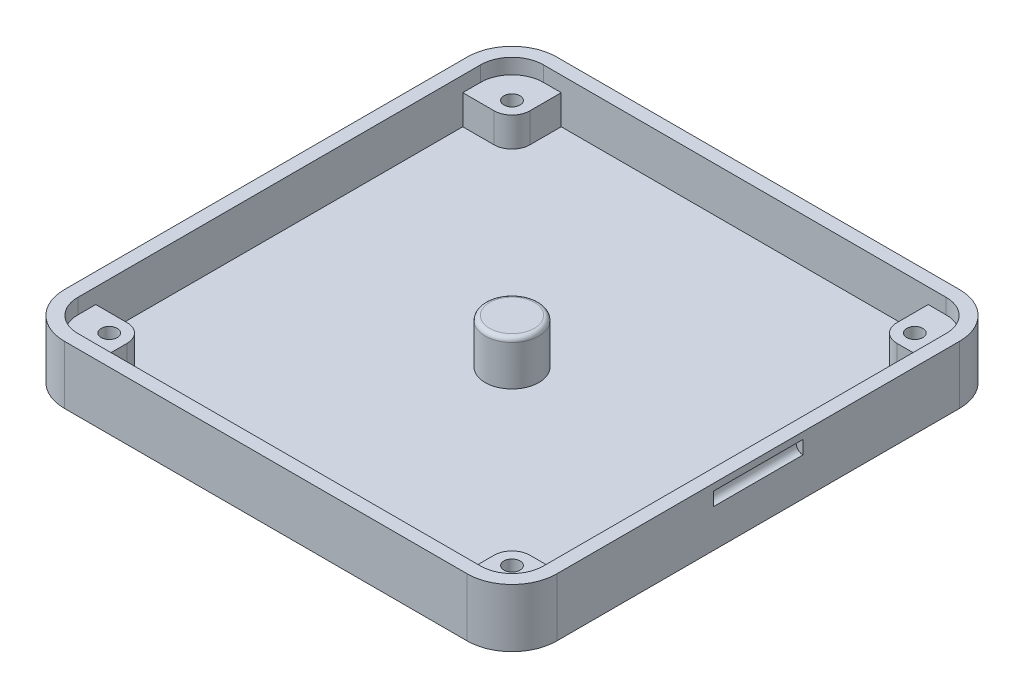
SolidWorks part; units mm, degrees
ref_plane "Front Plane" through (0, 0, 0) normal (0, 0, 1) x (1, 0, 0)
ref_plane "Top Plane" through (0, 0, 0) normal (0, 1, 0) x (1, 0, 0)
ref_plane "Right Plane" through (0, 0, 0) normal (1, 0, 0) x (0, 0, -1)
sketch "Sketch1" plane through (0, 0, 0) normal (0, 1, 0) x (1, 0, 0)
  line L5 (-22.5, -27.5) -> (22.5, -27.5)
  line L6 (-27.5, -22.5) -> (-27.5, 22.5)
  line L7 (-22.5, 27.5) -> (22.5, 27.5)
  line L8 (27.5, -22.5) -> (27.5, 22.5)
  line L9 (-27.5, -27.5) -> (27.5, 27.5) construction
  line L10 (-27.5, 27.5) -> (27.5, -27.5) construction
  arc A0 (-27.5, 22.5) -> (-22.5, 27.5) centre (-22.5, 22.5) cw
  arc A1 (22.5, 27.5) -> (27.5, 22.5) centre (22.5, 22.5) cw
  arc A2 (22.5, -27.5) -> (27.5, -22.5) centre (22.5, -22.5) ccw
  arc A3 (-22.5, -27.5) -> (-27.5, -22.5) centre (-22.5, -22.5) cw
  point P0 (0, 0)
  dimension "D3" = 5
  dimension "D1" = 55
  dimension "D2" = 55
extrude "Boss-Extrude1" add sketch "Sketch1" along normal blind 1.5
sketch "Sketch2" plane through (0, 1.5, 0) normal (0, 1, 0) x (1, 0, 0)
  line L4 (-27.5, 22.5) -> (-27.5, -22.5)
  line L5 (-22.5, -27.5) -> (22.5, -27.5)
  line L6 (27.5, -22.5) -> (27.5, 22.5)
  line L7 (22.5, 27.5) -> (-22.5, 27.5)
  line L8 (-26, 22.5) -> (-26, -22.5)
  line L9 (-22.5, -26) -> (22.5, -26)
  line L10 (26, -22.5) -> (26, 22.5)
  line L11 (22.5, 26) -> (-22.5, 26)
  line L12 (-26, 22.5) -> (-26, -22.5)
  line L13 (-22.5, -26) -> (22.5, -26)
  line L14 (26, -22.5) -> (26, 22.5)
  line L15 (22.5, 26) -> (-22.5, 26)
  arc A4 (-27.5, -22.5) -> (-22.5, -27.5) centre (-22.5, -22.5) ccw
  arc A5 (22.5, -27.5) -> (27.5, -22.5) centre (22.5, -22.5) ccw
  arc A6 (27.5, 22.5) -> (22.5, 27.5) centre (22.5, 22.5) ccw
  arc A7 (-22.5, 27.5) -> (-27.5, 22.5) centre (-22.5, 22.5) ccw
  arc A8 (-22.5, 26) -> (-26, 22.5) centre (-22.5, 22.5) ccw
  arc A9 (-26, -22.5) -> (-22.5, -26) centre (-22.5, -22.5) ccw
  arc A10 (22.5, -26) -> (26, -22.5) centre (22.5, -22.5) ccw
  arc A11 (26, 22.5) -> (22.5, 26) centre (22.5, 22.5) ccw
  arc A12 (-22.5, 26) -> (-26, 22.5) centre (-22.5, 22.5) ccw
  arc A13 (-26, -22.5) -> (-22.5, -26) centre (-22.5, -22.5) ccw
  arc A14 (22.5, -26) -> (26, -22.5) centre (22.5, -22.5) ccw
  arc A15 (26, 22.5) -> (22.5, 26) centre (22.5, 22.5) ccw
  dimension "D1" = 1.5
extrude "Boss-Extrude2" add sketch "Sketch2" along normal blind 5
sketch "Sketch5" plane through (0, 1.5, 0) normal (0, 1, 0) x (1, 0, 0)
  circle A0 centre (0, 0) radius 3
  dimension "D1" = 6
extrude "Boss-Extrude3" add sketch "Sketch5" along normal blind 5
sketch "Sketch6" plane through (0, 1.5, 0) normal (0, 1, 0) x (1, 0, 0)
  line L0 (-20.5, 26) -> (-20.5, 22.5)
  line L1 (22.5, 26) -> (-22.5, 26) construction
  line L2 (-22.5, 20.5) -> (-26, 20.5)
  line L4 (-26, 22.5) -> (-26, -22.5) construction
  line L5 (-26, 20.5) -> (-26, 22.5)
  line L6 (-22.5, 26) -> (-20.5, 26)
  line L7 (0, -14.905) -> (0, 14.905) construction
  line L8 (22.5, 26) -> (20.5, 26)
  line L9 (26, 20.5) -> (26, 22.5)
  line L10 (22.5, 20.5) -> (26, 20.5)
  line L11 (20.5, 26) -> (20.5, 22.5)
  line L12 (-14.905, 0) -> (14.905, 0) construction
  line L13 (20.5, -26) -> (20.5, -22.5)
  line L14 (22.5, -20.5) -> (26, -20.5)
  line L15 (26, -20.5) -> (26, -22.5)
  line L16 (22.5, -26) -> (20.5, -26)
  line L17 (-22.5, -26) -> (-20.5, -26)
  line L18 (-26, -20.5) -> (-26, -22.5)
  line L19 (-22.5, -20.5) -> (-26, -20.5)
  line L20 (-20.5, -26) -> (-20.5, -22.5)
  arc A0 (-20.5, 22.5) -> (-22.5, 20.5) centre (-22.5, 22.5) cw
  circle A1 centre (-22.5, 22.5) radius 0.9
  arc A2 (-26, 22.5) -> (-22.5, 26) centre (-22.5, 22.5) cw
  arc A3 (26, 22.5) -> (22.5, 26) centre (22.5, 22.5) ccw
  circle A4 centre (22.5, 22.5) radius 0.9
  arc A5 (20.5, 22.5) -> (22.5, 20.5) centre (22.5, 22.5) ccw
  arc A6 (20.5, -22.5) -> (22.5, -20.5) centre (22.5, -22.5) cw
  circle A7 centre (22.5, -22.5) radius 0.9
  arc A8 (26, -22.5) -> (22.5, -26) centre (22.5, -22.5) cw
  arc A9 (-26, -22.5) -> (-22.5, -26) centre (-22.5, -22.5) ccw
  circle A10 centre (-22.5, -22.5) radius 0.9
  arc A11 (-20.5, -22.5) -> (-22.5, -20.5) centre (-22.5, -22.5) ccw
  dimension "D3" = 2
  dimension "D4" = 2
extrude "Boss-Extrude4" add sketch "Sketch6" along normal offset from surface (3.3 mm away) 1.7 up to face at (0, 6.5, 3)
fillet "Fillet1" radius 0.5 1 edges at (0, 6.5, 3)
sketch "Sketch7" plane through (0, 0, 0) normal (0, -1, 0) x (1, 0, 0)
  line L2 (0, -14.905) -> (0, 14.905) construction
  line L3 (14.905, 0) -> (-14.905, 0) construction
  circle A0 centre (-22.5, 22.5) radius 1.75
  circle A1 centre (22.5, 22.5) radius 1.75
  circle A2 centre (22.5, -22.5) radius 1.75
  circle A3 centre (-22.5, -22.5) radius 1.75
  dimension "D1" = 3.5
extrude "Cut-Extrude1" cut sketch "Sketch7" against normal blind 2
ref_plane "Plane1" through (0, 0, 0) normal (0, 0, 1) x (1, 0, 0)
sketch "Sketch9" plane through (0, 0, 0) normal (0, 0, 1) x (1, 0, 0)
  line L3 (-22.5, 6.5) -> (-27.5, 6.5) construction
  line L4 (0, 0) -> (0, 6.5) construction
  line L5 (-22.5, 6.5) -> (22.5, 6.5) construction
  circle A2 centre (-27.5, 5) radius 0.75
  circle A3 centre (27.5, 5) radius 0.75
  dimension "D1" = 1.5
  dimension "D2" = 27.5
  dimension "D3" = 1.5
extrude "Cut-Extrude2" cut sketch "Sketch9" against normal mid plane 10
